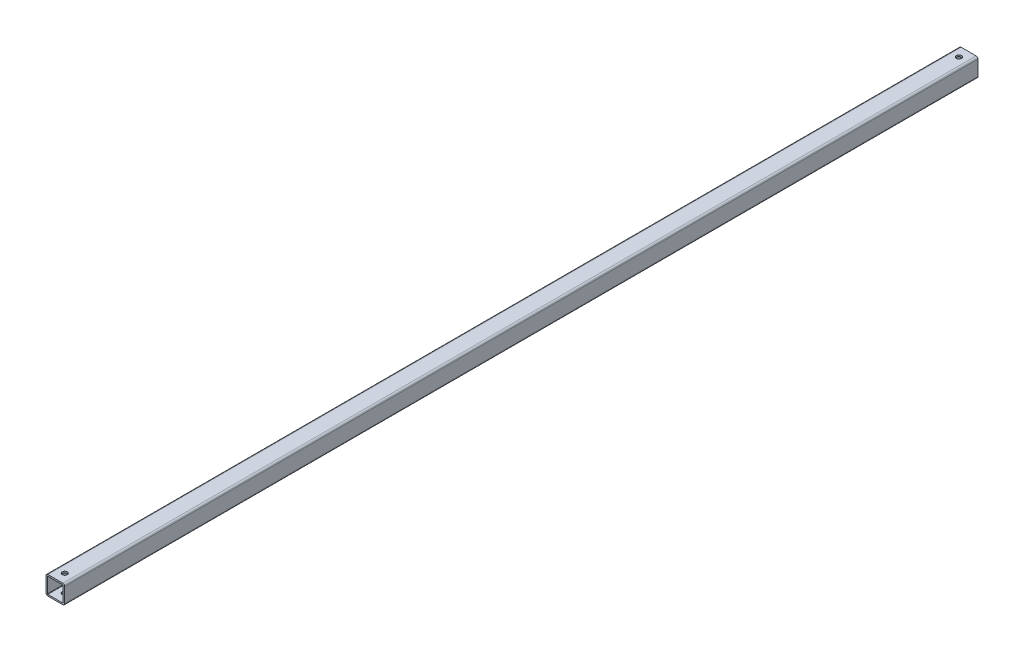
SolidWorks part; units mm, degrees
material "6063-T4"
ref_plane "Front Plane" through (0, 0, 0) normal (0, 0, 1) x (1, 0, 0)
ref_plane "Top Plane" through (0, 0, 0) normal (0, 1, 0) x (1, 0, 0)
ref_plane "Right Plane" through (0, 0, 0) normal (1, 0, 0) x (0, 0, -1)
sketch "Sketch1" plane through (0, 0, 0) normal (0, 0, 1) x (1, 0, 0)
  line L1 (10, -12.5) -> (-10, -12.5)
  line L2 (12.5, -10) -> (12.5, 10)
  line L3 (10, 12.5) -> (-10, 12.5)
  line L4 (-12.5, -10) -> (-12.5, 10)
  line L5 (12.5, -12.5) -> (-12.5, 12.5) construction
  line L6 (12.5, 12.5) -> (-12.5, -12.5) construction
  arc A0 (-10, 12.5) -> (-12.5, 10) centre (-10, 10) ccw
  arc A1 (12.5, 10) -> (10, 12.5) centre (10, 10) ccw
  arc A2 (10, -12.5) -> (12.5, -10) centre (10, -10) ccw
  arc A3 (-10, -12.5) -> (-12.5, -10) centre (-10, -10) cw
  point P0 (0, 0)
  dimension "D2" = 2.5
  dimension "D1" = 25
extrude "Extrude-Thin1" add sketch "Sketch1" along normal mid plane 1219.2 thin
hole_wizard "1/4 Clearance Hole1" positions "Sketch2" profile "Sketch3" hole size "1/4" standard "ANSI Inch"
sketch "Sketch2" plane through (0, 12.5, 0) normal (0, 1, 0) x (1, 0, 0)
  line L0 (12.5, -609.6) -> (12.5, 609.6) construction
  line L1 (10, 609.6) -> (-10, 609.6) construction
  line L2 (10, -609.6) -> (-10, -609.6) construction
  point P0 (-0.2, 596.9)
  point P7 (-0.2, -596.9)
  dimension "D1" = 12.7
  dimension "D2" = 12.7
  dimension "D3" = 12.7
  dimension "D4" = 12.7
sketch "Sketch3" plane through (-0.2, 12.5, -596.9) normal (1, 0, 0) x (0, 0, 1)
  line L0 (0, 0) -> (0, 27.4298)
  line L1 (0, 27.4298) -> (3.3782, 25.4)
  line L2 (3.3782, 25.4) -> (3.3782, 0)
  line L5 (3.3782, 0) -> (0, 0)
  line L10 (0, 27.4298) -> (-3.3782, 25.4) construction
  line L11 (0, -6.35) -> (0, 107.95) construction
  dimension "Hole Dia." = 6.7564
  dimension "Hole Depth" = 25.4
  dimension "Drill Angle" = 118
equation "\"D2@Sketch1\" = \"D5@Extrude-Thin1\" * 1.25"
